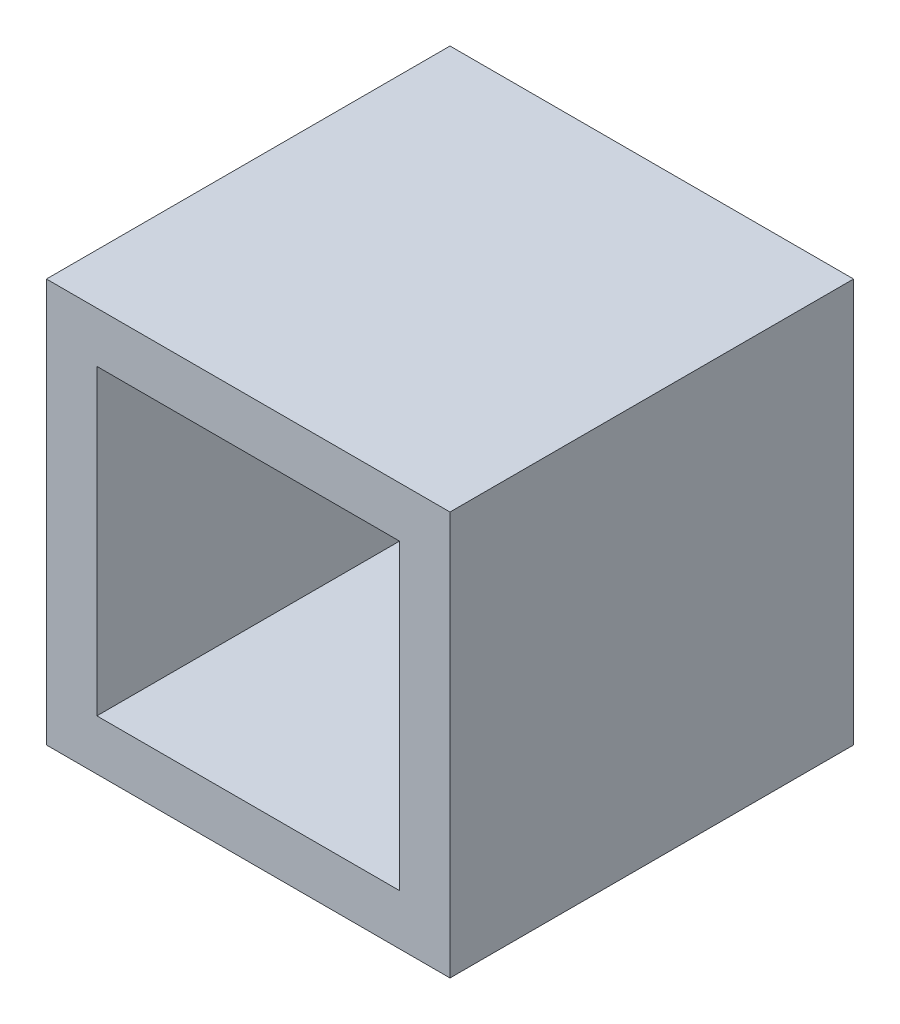
SolidWorks part; units mm, degrees
material "6061 Alloy"
ref_plane "Front Plane" through (0, 0, 0) normal (0, 0, 1) x (1, 0, 0)
ref_plane "Top Plane" through (0, 0, 0) normal (0, 1, 0) x (1, 0, 0)
ref_plane "Right Plane" through (0, 0, 0) normal (1, 0, 0) x (0, 0, -1)
sketch "Sketch1" plane through (0, 0, 0) normal (0, 0, 1) x (1, 0, 0)
  line L0 (-9.525, -9.525) -> (-9.525, 9.525)
  line L1 (-12.7, -12.7) -> (12.7, -12.7)
  line L2 (-12.7, -12.7) -> (-12.7, 12.7)
  line L3 (-12.7, 12.7) -> (12.7, 12.7)
  line L4 (12.7, -12.7) -> (12.7, 12.7)
  line L5 (-12.7, -12.7) -> (12.7, 12.7) construction
  line L6 (-12.7, 12.7) -> (12.7, -12.7) construction
  line L7 (-9.525, 9.525) -> (9.525, 9.525)
  line L8 (9.525, -9.525) -> (9.525, 9.525)
  line L9 (-9.525, -9.525) -> (9.525, -9.525)
  point P0 (0, 0)
  dimension "D1" = 25.4
  dimension "D2" = 3.175
extrude "Boss-Extrude1" add sketch "Sketch1" along normal blind 25.4
